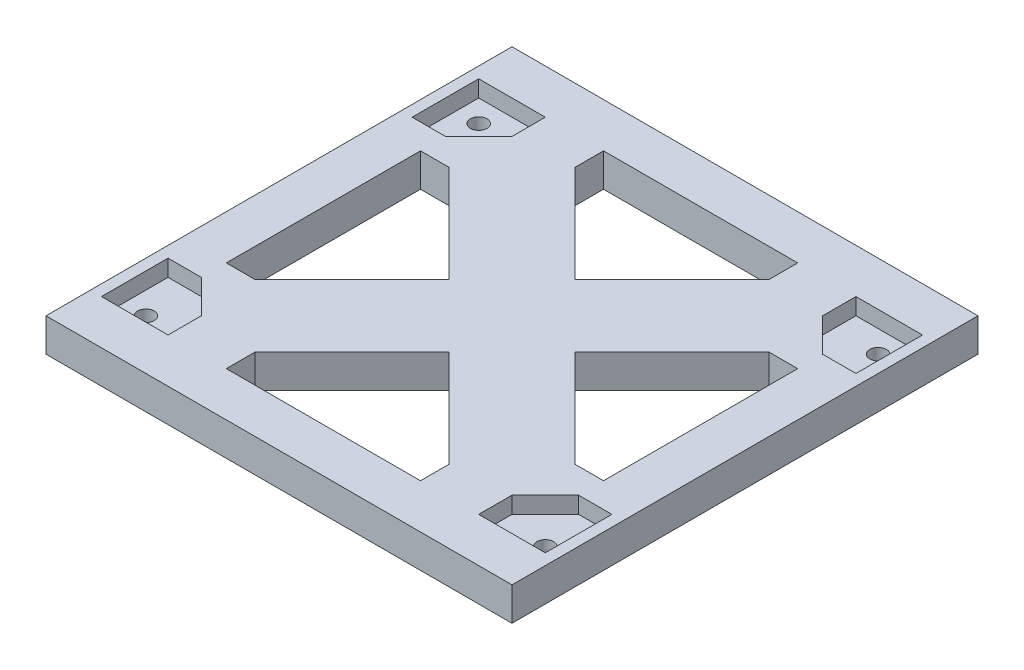
SolidWorks part; units mm, degrees
ref_plane "Front Plane" through (0, 0, 0) normal (0, 0, 1) x (1, 0, 0)
ref_plane "Top Plane" through (0, 0, 0) normal (0, 1, 0) x (1, 0, 0)
ref_plane "Right Plane" through (0, 0, 0) normal (1, 0, 0) x (0, 0, -1)
sketch "Sketch1" plane through (0, 0, 0) normal (0, 1, 0) x (1, 0, 0)
  line L1 (0, 0) -> (84, 0)
  line L2 (0, 0) -> (0, 84)
  line L3 (0, 84) -> (84, 84)
  line L4 (84, 0) -> (84, 84)
  dimension "D1" = 84
  dimension "D2" = 84
extrude "Boss-Extrude1" add sketch "Sketch1" along normal blind 6
sketch "Sketch2" plane through (0, 6, 0) normal (0, 1, 0) x (1, 0, 0)
  line L0 (84, 84) -> (0, 84) construction
  line L1 (0, 84) -> (0, 0) construction
  line L2 (0, 0) -> (84, 0) construction
  line L3 (84, 0) -> (84, 84) construction
  circle A0 centre (6, 72) radius 1.5
  circle A1 centre (6, 12) radius 1.5
  circle A2 centre (78, 12) radius 1.5
  circle A3 centre (78, 72) radius 1.5
  dimension "D1" = 3
  dimension "D2" = 3
  dimension "D3" = 3
  dimension "D4" = 3
  dimension "D6" = 6
  dimension "D7" = 12
  dimension "D8" = 6
  dimension "D9" = 6
  dimension "D10" = 12
  dimension "D11" = 6
  dimension "D5" = 12
  dimension "D12" = 12
extrude "Cut-Extrude1" cut sketch "Sketch2" against normal through all
sketch "Sketch3" plane through (0, 6, 0) normal (0, 1, 0) x (1, 0, 0)
  line L0 (24.5, 76) -> (59.5, 76)
  line L1 (59.5, 76) -> (59.5, 70.8137)
  line L2 (59.5, 70.8137) -> (42, 53.3137)
  line L3 (42, 53.3137) -> (24.5, 70.8137)
  line L4 (24.5, 70.8137) -> (24.5, 76)
  line L5 (24.5, 70.8137) -> (59.5, 70.8137) construction
  line L6 (42, 53.3137) -> (42, 76) construction
  line L8 (42, 84) -> (42, 76) construction
  line L9 (84, 84) -> (0, 84) construction
  line L10 (0, 84) -> (84, 0) construction
  line L11 (0, 0) -> (84, 84) construction
  dimension "D1" = 35
  dimension "D2" = 8
  dimension "D3" = 8
extrude "Cut-Extrude2" cut sketch "Sketch3" against normal through all
ref_plane "Plane1" through (0, 0, -42) normal (0, 0, 1) x (1, 0, 0)
mirror "Mirror1" about plane through (0, 0, -42) normal (0, 0, 1) of "Cut-Extrude2"
pattern_circular "CirPattern1" count 3 every 90 about axis through (42, 0, -42) along (0, 1, 0) of "Mirror1", "Cut-Extrude2"
sketch "Sketch4" plane through (0, 6, 0) normal (0, 1, 0) x (1, 0, 0)
  line L0 (2, 20) -> (2, 8)
  line L1 (2, 8) -> (14, 8)
  line L2 (14, 14) -> (8, 20)
  line L3 (2, 20) -> (8, 20)
  line L4 (8, 20) -> (14, 14)
  line L5 (14, 14) -> (14, 8)
  line L6 (0, 84) -> (0, 0) construction
  line L7 (0, 0) -> (84, 0) construction
  circle A0 centre (6, 12) radius 1.5
  circle A1 centre (6, 12) radius 1.5 construction
  circle M21 centre (6, 12) radius 1.5
  dimension "D1" = 2
  dimension "D2" = 8
  dimension "D3" = 12
  dimension "D4" = 12
  dimension "D5" = 6
  dimension "D6" = 6
extrude "Cut-Extrude4" cut sketch "Sketch4" against normal blind 3 contours L5 L2 L3 L0 L1 M21
mirror "Mirror2" about plane through (0, 0, -42) normal (0, 0, 1) of "Cut-Extrude4"
ref_plane "Plane2" through (42, 0, 0) normal (-1, 0, 0) x (0, 0, 1)
mirror "Mirror3" about plane through (42, 0, 0) normal (-1, 0, 0) of "Mirror2", "Cut-Extrude4"
